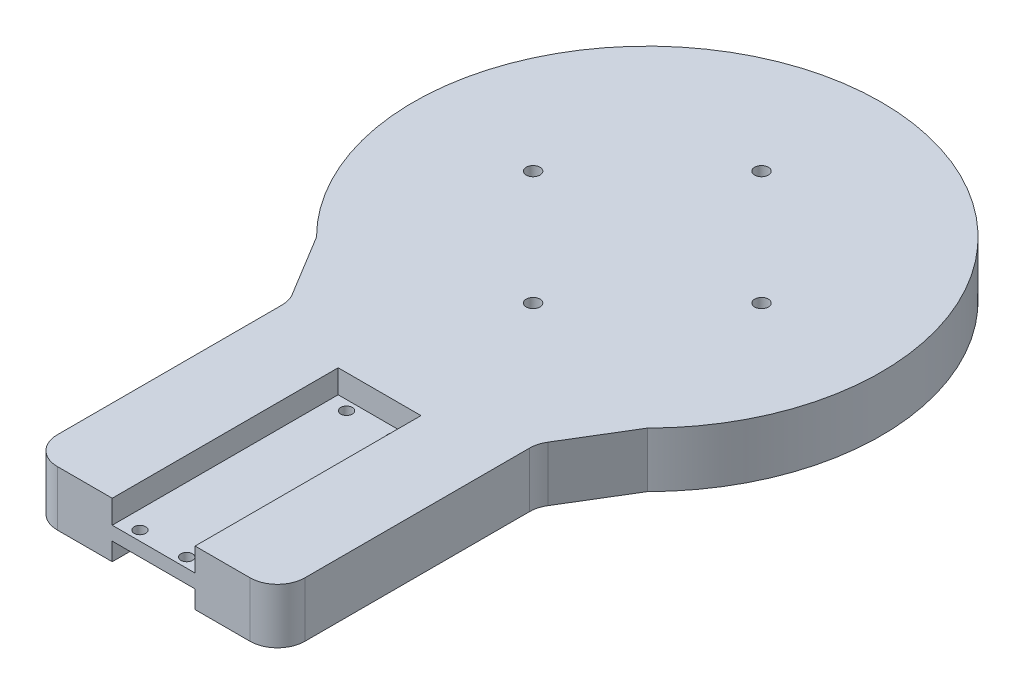
SolidWorks part; units mm, degrees
ref_plane "Front Plane" through (0, 0, 0) normal (0, 0, 1) x (1, 0, 0)
ref_plane "Top Plane" through (0, 0, 0) normal (0, 1, 0) x (1, 0, 0)
ref_plane "Right Plane" through (0, 0, 0) normal (1, 0, 0) x (0, 0, -1)
sketch "Sketch1" plane through (0, 0, 0) normal (0, 1, 0) x (1, 0, 0)
  line L0 (0, 85) -> (0, -179.39) construction
  line L1 (-85, 85) -> (85, 85) construction
  line L2 (-85, 85) -> (-85, -85) construction
  line L3 (-85, -85) -> (-45, -85) construction
  line L4 (85, 85) -> (85, -85) construction
  line L5 (-85, 85) -> (85, -85) construction
  line L6 (-85, -85) -> (85, 85) construction
  line L7 (-85, 0) -> (85, 0) construction
  line L8 (0, -47.195) -> (0, -179.39) construction
  line L9 (-45, -85) -> (-45, -179.39) construction
  line L10 (-45, -179.39) -> (45, -179.39) construction
  line L11 (45, -179.39) -> (45, -85) construction
  line L12 (45, -85) -> (85, -85) construction
  line L13 (60.1041, -60.1041) -> (46.4504, -82.6093)
  line L14 (-60.1041, -60.1041) -> (-46.4504, -82.6093)
  line L15 (-45, -87.7963) -> (-45, -118.89)
  line L16 (45, -87.7963) -> (45, -118.89)
  line L17 (-45, -118.89) -> (-45, -169.39)
  line L18 (-35, -179.39) -> (35, -179.39)
  line L19 (45, -169.39) -> (45, -118.89)
  circle A0 centre (0, 41.5) radius 2.5
  circle A1 centre (41.5, 0) radius 2.5
  circle A2 centre (0, -41.5) radius 2.5
  circle A3 centre (-41.5, 0) radius 2.5
  arc A4 (60.1041, -60.1041) -> (-60.1041, -60.1041) centre (0, 0) ccw
  arc A7 (35, -179.39) -> (45, -169.39) centre (35, -169.39) ccw
  arc A8 (-45, -169.39) -> (-35, -179.39) centre (-35, -169.39) ccw
  arc A9 (-45, -87.7963) -> (-46.4504, -82.6093) centre (-55, -87.7963) ccw
  arc A10 (45, -87.7963) -> (46.4504, -82.6093) centre (55, -87.7963) cw
  point P0 (0, 0)
  point P21 (0, 0)
  point P23 (0, -179.39)
  point P26 (0, -118.89)
  point P30 (60.1041, -60.1041)
  point P31 (-60.1041, -60.1041)
  point P32 (45, -118.89)
  point P33 (-45, -118.89)
  dimension "D3" = 5
  dimension "D8" = 170
  dimension "D10" = 10
  dimension "D11" = 10
  dimension "D1" = 170
  dimension "D2" = 170
  dimension "D4" = 41.5
  dimension "D6" = 179.39
  dimension "D7" = 90
  dimension "D9" = 60.5
  dimension "D5" = 4
extrude "Boss-Extrude1" add sketch "Sketch1" along normal blind 20
sketch "Sketch2" plane through (0, 20, 0) normal (0, 1, 0) x (1, 0, 0)
  line L0 (-35, -179.39) -> (35, -179.39) construction
  line L1 (-15.05, -97.29) -> (15.05, -97.29)
  line L2 (-15.05, -97.29) -> (-15.05, -179.39)
  line L3 (-15.05, -179.39) -> (15.05, -179.39)
  line L4 (15.05, -97.29) -> (15.05, -179.39)
  line L5 (-15.05, -97.29) -> (15.05, -179.39) construction
  line L6 (-15.05, -179.39) -> (15.05, -97.29) construction
  point P0 (0, -138.34)
  point P7 (0, -179.39)
  dimension "D1" = 82.1
  dimension "D2" = 30.1
extrude "Cut-Extrude1" cut sketch "Sketch2" against normal blind 8.5
sketch "Sketch3" plane through (0, 0, 0) normal (0, -1, 0) x (1, 0, 0)
  line L4 (-15.05, 97.29) -> (15.05, 97.29)
  line L5 (15.05, 97.29) -> (15.05, 179.39)
  line L6 (15.05, 179.39) -> (-15.05, 179.39)
  line L7 (-15.05, 179.39) -> (-15.05, 97.29)
  line L8 (-15.05, 97.29) -> (15.05, 97.29)
  line L9 (15.05, 97.29) -> (15.05, 179.39)
  line L10 (15.05, 179.39) -> (-15.05, 179.39)
  line L11 (-15.05, 179.39) -> (-15.05, 97.29)
  dimension "D1" = 0
extrude "Cut-Extrude2" cut sketch "Sketch3" against normal blind 6.5
sketch "Sketch5" plane through (0, 11.5, 0) normal (0, 1, 0) x (1, 0, 0)
  line L0 (-15.05, -179.39) -> (15.05, -179.39) construction
  line L1 (15.05, -179.39) -> (15.05, -97.29) construction
  line L2 (-15.05, -97.29) -> (-15.05, -179.39) construction
  line L3 (15.05, -97.29) -> (-15.05, -97.29) construction
  line L4 (-15.05, -179.39) -> (15.05, -179.39) construction
  line L5 (15.05, -179.39) -> (15.05, -97.29) construction
  line L6 (-15.05, -97.29) -> (-15.05, -179.39) construction
  line L7 (15.05, -97.29) -> (-15.05, -97.29) construction
  line L8 (0, -97.29) -> (0, -179.39) construction
  line L9 (-15.05, -138.34) -> (15.05, -138.34) construction
  circle A0 centre (-8.5, -100.8) radius 2.1
  circle A1 centre (8.5, -100.8) radius 2.1
  circle A2 centre (8.5, -175.88) radius 2.1
  circle A3 centre (-8.5, -175.88) radius 2.1
  point P12 (9.1177, -100.8)
  dimension "D3" = 4.2
  dimension "D1" = 8.5
  dimension "D2" = 3.51
  dimension "D4" = 17
extrude "Cut-Extrude3" cut sketch "Sketch5" against normal up to next
